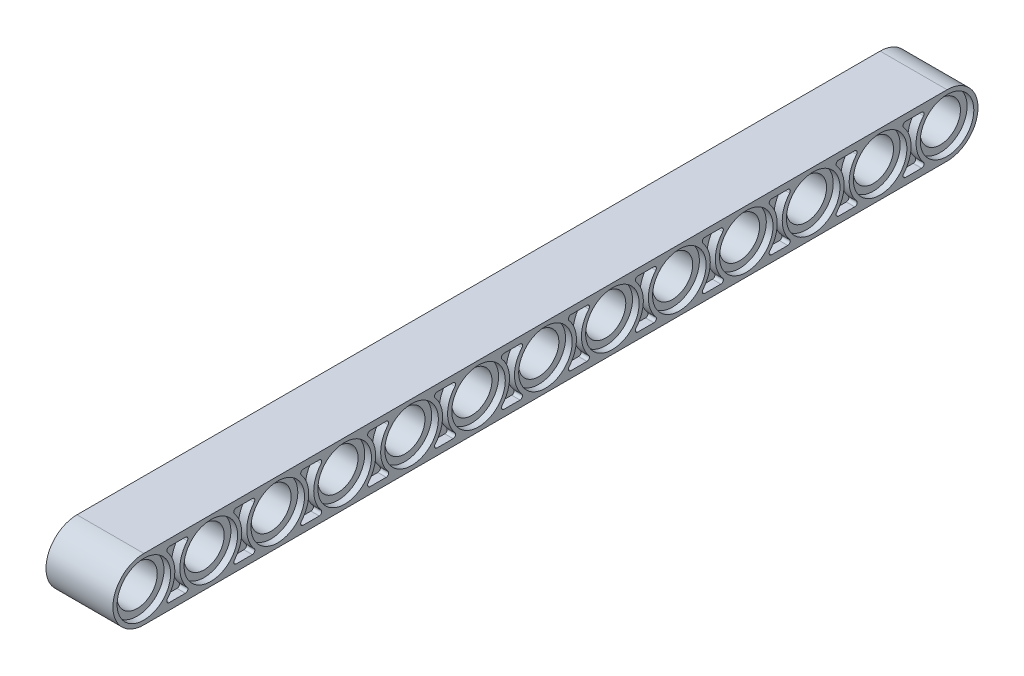
SolidWorks part; units mm, degrees
ref_plane "Front Plane" through (0, 0, 0) normal (0, 0, 1) x (1, 0, 0)
ref_plane "Top Plane" through (0, 0, 0) normal (0, 1, 0) x (1, 0, 0)
ref_plane "Right Plane" through (0, 0, 0) normal (1, 0, 0) x (0, 0, -1)
sketch "Sketch1" plane through (0, 0, 0) normal (1, 0, 0) x (0, 0, -1)
  line L0 (-34.04, 0) -> (61.96, 0) construction
  line L1 (-34.04, 3.7) -> (61.96, 3.7)
  line L2 (-34.04, -3.7) -> (61.96, -3.7)
  arc A0 (-34.04, 3.7) -> (-34.04, -3.7) centre (-34.04, 0) ccw
  arc A1 (61.96, -3.7) -> (61.96, 3.7) centre (61.96, 0) ccw
  circle A2 centre (-34.04, 0) radius 2.4
  circle A3 centre (-26.04, 0) radius 2.4
  circle A4 centre (-18.04, 0) radius 2.4
  circle A5 centre (-10.04, 0) radius 2.4
  circle A6 centre (-2.04, 0) radius 2.4
  circle A7 centre (5.96, 0) radius 2.4
  circle A8 centre (13.96, 0) radius 2.4
  circle A9 centre (21.96, 0) radius 2.4
  circle A10 centre (29.96, 0) radius 2.4
  circle A11 centre (37.96, 0) radius 2.4
  circle A12 centre (45.96, 0) radius 2.4
  circle A13 centre (53.96, 0) radius 2.4
  circle A14 centre (61.96, 0) radius 2.4
  point P3 (13.96, 0)
  dimension "D3" = 13
  dimension "D1" = 7.4
  dimension "D2" = 96
extrude "Boss-Extrude1" add sketch "Sketch1" along normal blind 8
sketch "Sketch2" plane through (8, 0, 0) normal (1, 0, 0) x (0, 0, -1)
  circle A0 centre (-34.04, 0) radius 3.2
  circle A1 centre (-26.04, 0) radius 3.2
  circle A2 centre (-18.04, 0) radius 3.2
  circle A3 centre (-10.04, 0) radius 3.2
  circle A4 centre (-2.04, 0) radius 3.2
  circle A5 centre (5.96, 0) radius 3.2
  circle A6 centre (13.96, 0) radius 3.2
  circle A7 centre (21.96, 0) radius 3.2
  circle A8 centre (29.96, 0) radius 3.2
  circle A9 centre (37.96, 0) radius 3.2
  circle A10 centre (45.96, 0) radius 3.2
  circle A11 centre (53.96, 0) radius 3.2
  circle A12 centre (61.96, 0) radius 3.2
  dimension "D1" = 13
extrude "Cut-Extrude1" cut sketch "Sketch2" against normal blind 0.8
ref_plane "Plane1" through (4, 0, 0) normal (1, 0, 0) x (0, 0, -1)
sketch "Sketch4" plane through (8, 0, 0) normal (1, 0, 0) x (0, 0, -1)
  line L0 (-31.0003, 2.9) -> (-29.0797, 2.9)
  line L1 (61.96, 3.7) -> (-34.04, 3.7) construction
  line L2 (-34.04, 0) -> (-41.4341, 0) construction
  line L3 (-31.0003, -2.9) -> (-29.0797, -2.9)
  line L4 (-23.0003, 2.9) -> (-21.0797, 2.9)
  line L5 (-23.0003, -2.9) -> (-21.0797, -2.9)
  line L6 (-15.0003, 2.9) -> (-13.0797, 2.9)
  line L7 (-15.0003, -2.9) -> (-13.0797, -2.9)
  line L8 (-7.0003, 2.9) -> (-5.0797, 2.9)
  line L9 (-7.0003, -2.9) -> (-5.0797, -2.9)
  line L10 (0.9997, 2.9) -> (2.9203, 2.9)
  line L11 (0.9997, -2.9) -> (2.9203, -2.9)
  line L12 (8.9997, 2.9) -> (10.9203, 2.9)
  line L13 (8.9997, -2.9) -> (10.9203, -2.9)
  line L14 (16.9997, 2.9) -> (18.9203, 2.9)
  line L15 (16.9997, -2.9) -> (18.9203, -2.9)
  line L16 (24.9997, 2.9) -> (26.9203, 2.9)
  line L17 (24.9997, -2.9) -> (26.9203, -2.9)
  line L18 (32.9997, 2.9) -> (34.9203, 2.9)
  line L19 (32.9997, -2.9) -> (34.9203, -2.9)
  line L20 (40.9997, 2.9) -> (42.9203, 2.9)
  line L21 (40.9997, -2.9) -> (42.9203, -2.9)
  line L22 (48.9997, 2.9) -> (50.9203, 2.9)
  line L23 (48.9997, -2.9) -> (50.9203, -2.9)
  line L24 (56.9997, 2.9) -> (58.9203, 2.9)
  line L25 (56.9997, -2.9) -> (58.9203, -2.9)
  arc A0 (-31.2282, -2.405) -> (-31.2282, 2.405) centre (-34.04, 0) ccw
  arc A1 (-28.8518, 2.405) -> (-28.8518, -2.405) centre (-26.04, 0) ccw
  arc A2 (-31.2282, 2.405) -> (-31.0003, 2.9) centre (-31.0003, 2.6) cw
  arc A3 (-28.8518, 2.405) -> (-29.0797, 2.9) centre (-29.0797, 2.6) ccw
  arc A4 (-28.8518, -2.405) -> (-29.0797, -2.9) centre (-29.0797, -2.6) cw
  arc A5 (-31.2282, -2.405) -> (-31.0003, -2.9) centre (-31.0003, -2.6) ccw
  arc A6 (-23.2282, -2.405) -> (-23.2282, 2.405) centre (-26.04, 0) ccw
  arc A7 (-20.8518, 2.405) -> (-20.8518, -2.405) centre (-18.04, 0) ccw
  arc A8 (-23.2282, 2.405) -> (-23.0003, 2.9) centre (-23.0003, 2.6) cw
  arc A9 (-20.8518, 2.405) -> (-21.0797, 2.9) centre (-21.0797, 2.6) ccw
  arc A10 (-20.8518, -2.405) -> (-21.0797, -2.9) centre (-21.0797, -2.6) cw
  arc A11 (-23.2282, -2.405) -> (-23.0003, -2.9) centre (-23.0003, -2.6) ccw
  arc A12 (-15.2282, -2.405) -> (-15.2282, 2.405) centre (-18.04, 0) ccw
  arc A13 (-12.8518, 2.405) -> (-12.8518, -2.405) centre (-10.04, 0) ccw
  arc A14 (-15.2282, 2.405) -> (-15.0003, 2.9) centre (-15.0003, 2.6) cw
  arc A15 (-12.8518, 2.405) -> (-13.0797, 2.9) centre (-13.0797, 2.6) ccw
  arc A16 (-12.8518, -2.405) -> (-13.0797, -2.9) centre (-13.0797, -2.6) cw
  arc A17 (-15.2282, -2.405) -> (-15.0003, -2.9) centre (-15.0003, -2.6) ccw
  arc A18 (-7.2282, -2.405) -> (-7.2282, 2.405) centre (-10.04, 0) ccw
  arc A19 (-4.8518, 2.405) -> (-4.8518, -2.405) centre (-2.04, 0) ccw
  arc A20 (-7.2282, 2.405) -> (-7.0003, 2.9) centre (-7.0003, 2.6) cw
  arc A21 (-4.8518, 2.405) -> (-5.0797, 2.9) centre (-5.0797, 2.6) ccw
  arc A22 (-4.8518, -2.405) -> (-5.0797, -2.9) centre (-5.0797, -2.6) cw
  arc A23 (-7.2282, -2.405) -> (-7.0003, -2.9) centre (-7.0003, -2.6) ccw
  arc A24 (0.7718, -2.405) -> (0.7718, 2.405) centre (-2.04, 0) ccw
  arc A25 (3.1482, 2.405) -> (3.1482, -2.405) centre (5.96, 0) ccw
  arc A26 (0.7718, 2.405) -> (0.9997, 2.9) centre (0.9997, 2.6) cw
  arc A27 (3.1482, 2.405) -> (2.9203, 2.9) centre (2.9203, 2.6) ccw
  arc A28 (3.1482, -2.405) -> (2.9203, -2.9) centre (2.9203, -2.6) cw
  arc A29 (0.7718, -2.405) -> (0.9997, -2.9) centre (0.9997, -2.6) ccw
  arc A30 (8.7718, -2.405) -> (8.7718, 2.405) centre (5.96, 0) ccw
  arc A31 (11.1482, 2.405) -> (11.1482, -2.405) centre (13.96, 0) ccw
  arc A32 (8.7718, 2.405) -> (8.9997, 2.9) centre (8.9997, 2.6) cw
  arc A33 (11.1482, 2.405) -> (10.9203, 2.9) centre (10.9203, 2.6) ccw
  arc A34 (11.1482, -2.405) -> (10.9203, -2.9) centre (10.9203, -2.6) cw
  arc A35 (8.7718, -2.405) -> (8.9997, -2.9) centre (8.9997, -2.6) ccw
  arc A36 (16.7718, -2.405) -> (16.7718, 2.405) centre (13.96, 0) ccw
  arc A37 (19.1482, 2.405) -> (19.1482, -2.405) centre (21.96, 0) ccw
  arc A38 (16.7718, 2.405) -> (16.9997, 2.9) centre (16.9997, 2.6) cw
  arc A39 (19.1482, 2.405) -> (18.9203, 2.9) centre (18.9203, 2.6) ccw
  arc A40 (19.1482, -2.405) -> (18.9203, -2.9) centre (18.9203, -2.6) cw
  arc A41 (16.7718, -2.405) -> (16.9997, -2.9) centre (16.9997, -2.6) ccw
  arc A42 (24.7718, -2.405) -> (24.7718, 2.405) centre (21.96, 0) ccw
  arc A43 (27.1482, 2.405) -> (27.1482, -2.405) centre (29.96, 0) ccw
  arc A44 (24.7718, 2.405) -> (24.9997, 2.9) centre (24.9997, 2.6) cw
  arc A45 (27.1482, 2.405) -> (26.9203, 2.9) centre (26.9203, 2.6) ccw
  arc A46 (27.1482, -2.405) -> (26.9203, -2.9) centre (26.9203, -2.6) cw
  arc A47 (24.7718, -2.405) -> (24.9997, -2.9) centre (24.9997, -2.6) ccw
  arc A48 (32.7718, -2.405) -> (32.7718, 2.405) centre (29.96, 0) ccw
  arc A49 (35.1482, 2.405) -> (35.1482, -2.405) centre (37.96, 0) ccw
  arc A50 (32.7718, 2.405) -> (32.9997, 2.9) centre (32.9997, 2.6) cw
  arc A51 (35.1482, 2.405) -> (34.9203, 2.9) centre (34.9203, 2.6) ccw
  arc A52 (35.1482, -2.405) -> (34.9203, -2.9) centre (34.9203, -2.6) cw
  arc A53 (32.7718, -2.405) -> (32.9997, -2.9) centre (32.9997, -2.6) ccw
  arc A54 (40.7718, -2.405) -> (40.7718, 2.405) centre (37.96, 0) ccw
  arc A55 (43.1482, 2.405) -> (43.1482, -2.405) centre (45.96, 0) ccw
  arc A56 (40.7718, 2.405) -> (40.9997, 2.9) centre (40.9997, 2.6) cw
  arc A57 (43.1482, 2.405) -> (42.9203, 2.9) centre (42.9203, 2.6) ccw
  arc A58 (43.1482, -2.405) -> (42.9203, -2.9) centre (42.9203, -2.6) cw
  arc A59 (40.7718, -2.405) -> (40.9997, -2.9) centre (40.9997, -2.6) ccw
  arc A60 (48.7718, -2.405) -> (48.7718, 2.405) centre (45.96, 0) ccw
  arc A61 (51.1482, 2.405) -> (51.1482, -2.405) centre (53.96, 0) ccw
  arc A62 (48.7718, 2.405) -> (48.9997, 2.9) centre (48.9997, 2.6) cw
  arc A63 (51.1482, 2.405) -> (50.9203, 2.9) centre (50.9203, 2.6) ccw
  arc A64 (51.1482, -2.405) -> (50.9203, -2.9) centre (50.9203, -2.6) cw
  arc A65 (48.7718, -2.405) -> (48.9997, -2.9) centre (48.9997, -2.6) ccw
  arc A66 (56.7718, -2.405) -> (56.7718, 2.405) centre (53.96, 0) ccw
  arc A67 (59.1482, 2.405) -> (59.1482, -2.405) centre (61.96, 0) ccw
  arc A68 (56.7718, 2.405) -> (56.9997, 2.9) centre (56.9997, 2.6) cw
  arc A69 (59.1482, 2.405) -> (58.9203, 2.9) centre (58.9203, 2.6) ccw
  arc A70 (59.1482, -2.405) -> (58.9203, -2.9) centre (58.9203, -2.6) cw
  arc A71 (56.7718, -2.405) -> (56.9997, -2.9) centre (56.9997, -2.6) ccw
  dimension "D2" = 0.3
  dimension "D1" = 0.8
  dimension "D3" = 12
extrude "Cut-Extrude2" cut sketch "Sketch4" against normal blind 1
mirror "Mirror1" about plane through (4, 0, 0) normal (1, 0, 0) of "Cut-Extrude1", "Cut-Extrude2"
